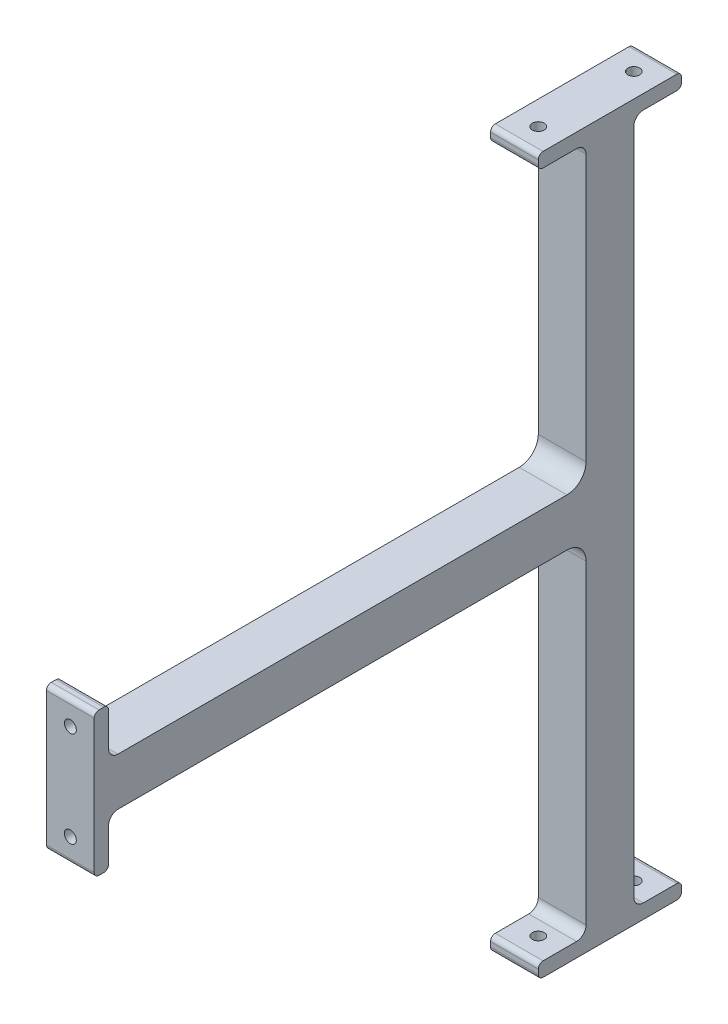
SolidWorks part; units mm, degrees
material "PLA"
ref_plane "Front Plane" through (0, 0, 0) normal (0, 0, 1) x (1, 0, 0)
ref_plane "Top Plane" through (0, 0, 0) normal (0, 1, 0) x (1, 0, 0)
ref_plane "Right Plane" through (0, 0, 0) normal (1, 0, 0) x (0, 0, -1)
sketch "Sketch1" plane through (0, 0, 0) normal (1, 0, 0) x (0, 0, -1)
  line L0 (0, 0) -> (-19.05, 0)
  line L1 (-19.05, 0) -> (-19.05, 3.81)
  line L2 (-19.05, 3.81) -> (-6.35, 3.81)
  line L3 (-6.35, 3.81) -> (-6.35, 95.25)
  line L4 (-6.35, 95.25) -> (-133.35, 95.25)
  line L5 (-133.35, 95.25) -> (-133.35, 82.55)
  line L6 (-133.35, 82.55) -> (-137.16, 82.55)
  line L7 (-137.16, 82.55) -> (-137.16, 120.65)
  line L8 (-137.16, 120.65) -> (-133.35, 120.65)
  line L9 (-133.35, 120.65) -> (-133.35, 107.95)
  line L10 (-133.35, 107.95) -> (-6.35, 107.95)
  line L11 (-6.35, 107.95) -> (-6.35, 186.436)
  line L12 (-6.35, 186.436) -> (-19.05, 186.436)
  line L13 (-19.05, 186.436) -> (-19.05, 190.246)
  line L14 (-19.05, 190.246) -> (19.05, 190.246)
  line L15 (19.05, 190.246) -> (19.05, 186.436)
  line L16 (19.05, 186.436) -> (6.35, 186.436)
  line L17 (6.35, 186.436) -> (6.35, 3.81)
  line L18 (6.35, 3.81) -> (19.05, 3.81)
  line L19 (19.05, 3.81) -> (19.05, 0)
  line L20 (19.05, 0) -> (0, 0)
  line L21 (-137.16, 101.6) -> (6.35, 101.6) construction
  line L22 (0, 0) -> (0, 190.246) construction
  dimension "D1" = 12.7
  dimension "D2" = 12.7
  dimension "D3" = 12.7
  dimension "D4" = 12.7
  dimension "D5" = 12.7
  dimension "D6" = 12.7
  dimension "D7" = 3.81
  dimension "D8" = 3.81
  dimension "D9" = 3.81
  dimension "D10" = 190.246
  dimension "D11" = 101.6
  dimension "D12" = 137.16
extrude "Boss-Extrude1" add sketch "Sketch1" along normal blind 12.7
sketch "Sketch2" plane through (0, 0, 137.16) normal (0, 0, 1) x (1, 0, 0)
  line L0 (12.7, 101.6) -> (0, 101.6) construction
  line L1 (12.7, 120.65) -> (12.7, 82.55) construction
  line L2 (0, 120.65) -> (0, 82.55) construction
  line L3 (6.35, 114.3) -> (6.35, 101.6) construction
  circle A0 centre (6.35, 114.3) radius 1.5875
  circle A1 centre (6.35, 88.9) radius 1.5875
  dimension "D1" = 3.175
  dimension "D2" = 25.4
extrude "Side_mount_holes" cut sketch "Sketch2" against normal blind 12.7
ref_plane "Plane1" through (0, 95.123, 0) normal (0, -1, 0) x (-1, 0, 0)
sketch "Sketch3" plane through (0, 0, 0) normal (0, -1, 0) x (1, 0, 0)
  line L0 (0, 0) -> (12.7, 0) construction
  line L1 (12.7, 19.05) -> (12.7, -19.05) construction
  line L2 (6.35, 0) -> (6.35, 19.05) construction
  line L3 (12.7, 19.05) -> (0, 19.05) construction
  circle A0 centre (6.35, 12.7) radius 1.5875
  circle A1 centre (6.35, -12.7) radius 1.5875
  dimension "D1" = 3.175
  dimension "D2" = 25.4
extrude "top_Bottom_mount_holes" cut sketch "Sketch3" against normal blind 12.7
mirror "Mirror1" about plane through (0, 95.123, 0) normal (0, -1, 0) of "top_Bottom_mount_holes"
fillet "Fillet1" radius 2.54 6 edges at (6.35, 186.436, -6.35) (6.35, 186.436, 6.35) (6.35, 95.25, 133.35) (6.35, 107.95, 133.35) (6.35, 3.81, -6.35) (6.35, 3.81, 6.35)
fillet "Fillet2" radius 5.08 2 edges at (6.35, 95.25, 6.35) (6.35, 107.95, 6.35)
fillet "Fillet3" radius 1.27 12 edges at (6.35, 190.246, 19.05) (6.35, 186.436, 19.05) (6.35, 186.436, -19.05) (6.35, 190.246, -19.05) (6.35, 120.65, 137.16) (6.35, 120.65, 133.35) (6.35, 82.55, 137.16) (6.35, 82.55, 133.35) (6.35, 3.81, -19.05) (6.35, 0, -19.05) (6.35, 3.81, 19.05) (6.35, 0, 19.05)
equation "\"D3@Sketch1\"=\"D2@Sketch1\""
equation "\"D4@Sketch1\"=\"D2@Sketch1\""
equation "\"D5@Sketch1\"=\"D1@Sketch1\""
equation "\"D6@Sketch1\"=\"D1@Sketch1\""
equation "\"D8@Sketch1\"=\"D7@Sketch1\""
equation "\"D9@Sketch1\"=\"D7@Sketch1\""
